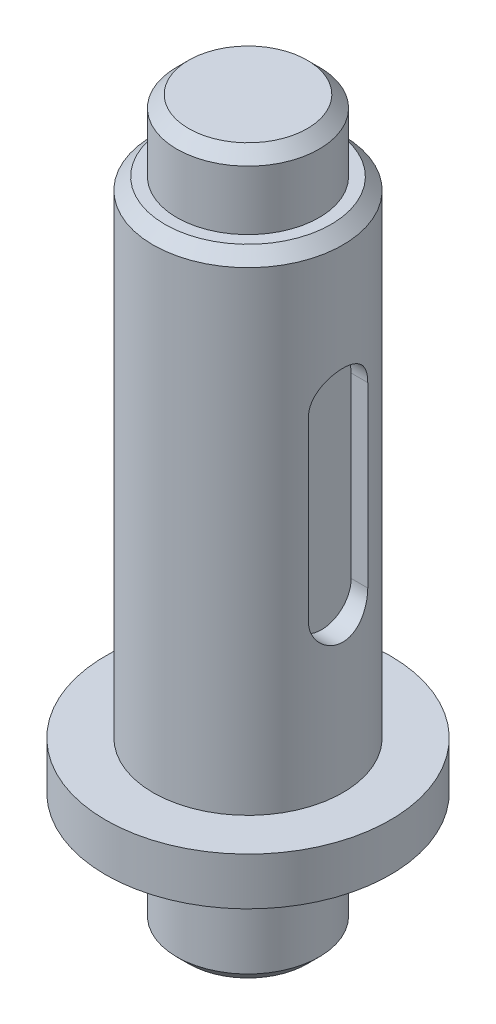
SolidWorks part; units mm, degrees
material "Alloy Steel"
ref_plane "Ön Düzlem" through (0, 0, 0) normal (0, 0, 1) x (1, 0, 0)
ref_plane "Üst Düzlem" through (0, 0, 0) normal (0, 1, 0) x (1, 0, 0)
ref_plane "Sağ Düzlem" through (0, 0, 0) normal (1, 0, 0) x (0, 0, -1)
sketch "Sketch1" plane through (0, 0, 0) normal (0, 1, 0) x (1, 0, 0)
  circle A0 centre (0, 0) radius 6
  dimension "D1" = 12
extrude "Boss-Extrude1" add sketch "Sketch1" along normal blind 10
sketch "Sketch2" plane through (0, 10, 0) normal (0, 1, 0) x (1, 0, 0)
  circle A0 centre (0, 0) radius 12
  dimension "D1" = 24
extrude "Boss-Extrude2" add sketch "Sketch2" along normal blind 4
sketch "Sketch3" plane through (0, 14, 0) normal (0, 1, 0) x (1, 0, 0)
  circle A0 centre (0, 0) radius 8
  dimension "D1" = 16
extrude "Boss-Extrude3" add sketch "Sketch3" along normal blind 41
sketch "Sketch4" plane through (0, 55, 0) normal (0, 1, 0) x (1, 0, 0)
  circle A0 centre (0, 0) radius 6
  dimension "D1" = 12
extrude "Boss-Extrude4" add sketch "Sketch4" along normal blind 6
chamfer "Chamfer1" distance 1 angle 45 1 edges at (0, 0, 6)
chamfer "Chamfer2" distance 1 angle 45 1 edges at (0, 61, 6)
chamfer "Chamfer3" distance 1 angle 45 1 edges at (0, 55, 8)
ref_plane "Plane1" through (8, 0, 0) normal (1, 0, 0) x (0, 0, -1)
sketch "Sketch5" plane through (8, 0, 0) normal (1, 0, 0) x (0, 0, -1)
  line L0 (0, 42.5) -> (0, 27.5) construction
  line L1 (2.5, 42.5) -> (2.5, 27.5)
  line L2 (-2.5, 42.5) -> (-2.5, 27.5)
  line L3 (12, 14) -> (-12, 14) construction
  arc A0 (2.5, 42.5) -> (-2.5, 42.5) centre (0, 42.5) ccw
  arc A1 (-2.5, 27.5) -> (2.5, 27.5) centre (0, 27.5) ccw
  point P3 (0, 35)
  dimension "D1" = 5
  dimension "D2" = 15
  dimension "D3" = 13.5
extrude "Cut-Extrude1" cut sketch "Sketch5" against normal blind 1.8
